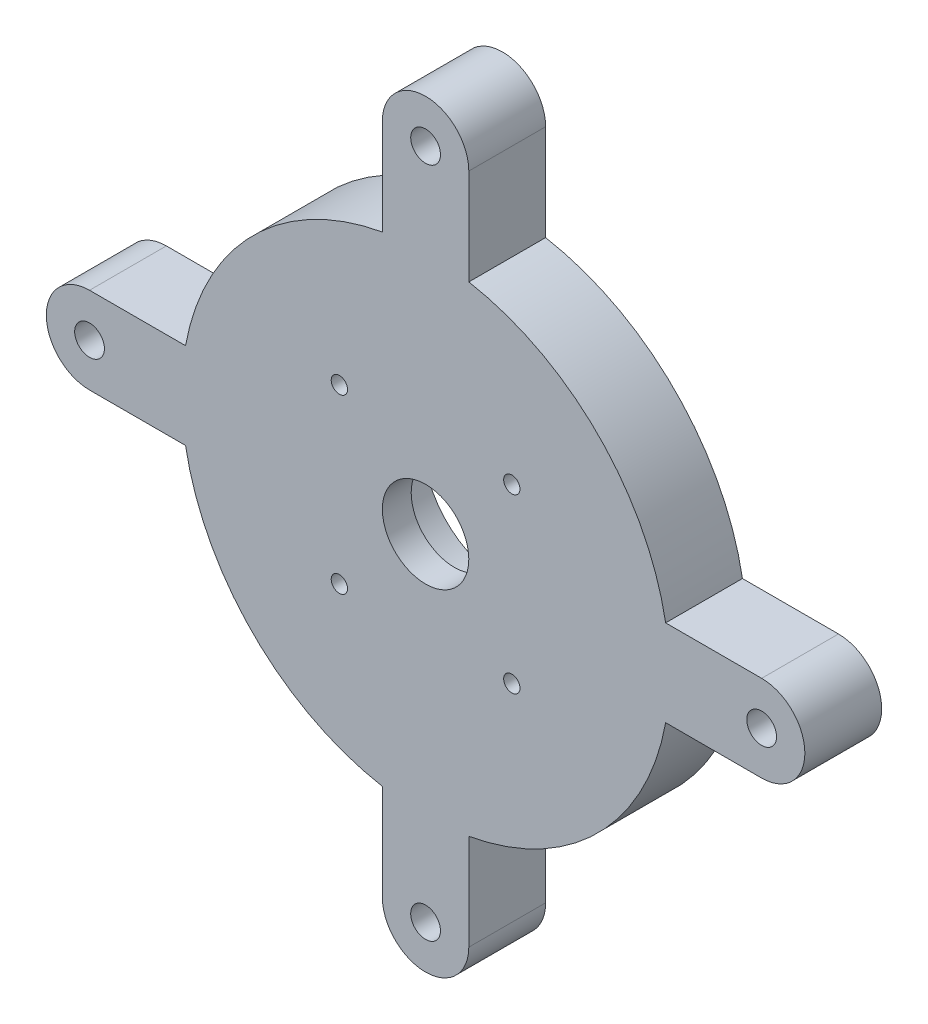
SolidWorks part; units mm, degrees
ref_plane "Front Plane" through (0, 0, 0) normal (0, 0, 1) x (1, 0, 0)
ref_plane "Top Plane" through (0, 0, 0) normal (0, 1, 0) x (1, 0, 0)
ref_plane "Right Plane" through (0, 0, 0) normal (1, 0, 0) x (0, 0, -1)
sketch "Sketch1" plane through (0, 0, 0) normal (0, 0, 1) x (1, 0, 0)
  line L11 (0, 0) -> (8.9803, 8.9803) construction
  line L14 (-25, -4.5) -> (-25, 4.5) construction
  line L17 (0, 0) -> (-25, 0) construction
  line L32 (-35, 4.5) -> (-25, 4.5)
  line L33 (-25, -4.5) -> (-35, -4.5)
  line L34 (-4.5, 25) -> (-4.5, 35)
  line L37 (4.5, 35) -> (4.5, 25)
  line L38 (25, 4.5) -> (35, 4.5)
  line L39 (35, -4.5) -> (25, -4.5)
  line L43 (4.5, -25) -> (4.5, -35)
  line L44 (-4.5, -35) -> (-4.5, -25)
  line L57 (-25, 0) -> (-35, 0) construction
  circle A2 centre (0, 0) radius 4.5
  circle A3 centre (0, 0) radius 12.7 construction
  circle A11 centre (8.9803, 8.9803) radius 0.85
  circle A12 centre (8.9803, -8.9803) radius 0.85
  circle A13 centre (-8.9803, -8.9803) radius 0.85
  circle A14 centre (-8.9803, 8.9803) radius 0.85
  arc A15 (-35, 4.5) -> (-35, -4.5) centre (-35, 0) ccw
  circle A16 centre (-35, 0) radius 1.55
  arc A23 (4.5, 35) -> (-4.5, 35) centre (0, 35) ccw
  circle A24 centre (0, 35) radius 1.55
  arc A25 (35, -4.5) -> (35, 4.5) centre (35, 0) ccw
  circle A26 centre (35, 0) radius 1.55
  arc A27 (-4.5, -35) -> (4.5, -35) centre (0, -35) ccw
  circle A28 centre (0, -35) radius 1.55
  arc A29 (-25, 4.5) -> (-4.5, 25) centre (0, 0) cw
  arc A30 (25, 4.5) -> (4.5, 25) centre (0, 0) ccw
  arc A31 (-25, -4.5) -> (-4.5, -25) centre (0, 0) ccw
  arc A32 (4.5, -25) -> (25, -4.5) centre (0, 0) ccw
  point P7 (0, 0)
  point P10 (0, 0)
  point P12 (0, 0)
  point P16 (0, 0)
  point P17 (0, 0)
  point P20 (0, 0)
  point P30 (0, 0)
  point P47 (0, 0)
  point P64 (0, 0)
  dimension "D1" = 4
  dimension "D2" = 4
extrude "Boss-Extrude2" add sketch "Sketch1" along normal blind 8
sketch "Sketch5" plane through (0, 0, 0) normal (0, 0, -1) x (-1, 0, 0)
  circle A0 centre (0, 0) radius 8.2
extrude "Cut-Extrude3" cut sketch "Sketch5" against normal blind 5
sketch "Sketch6" plane through (0, 0, 0) normal (0, 0, 1) x (1, 0, 0)
  circle A0 centre (0, 35) radius 3.5
  circle A1 centre (35, 0) radius 3.5
  circle A2 centre (0, -35) radius 3.5
  circle A3 centre (-35, 0) radius 3.5
  point P12 (0, 0)
  dimension "D1" = 4
extrude "Cut-Extrude6" cut sketch "Sketch6" along normal blind 2
